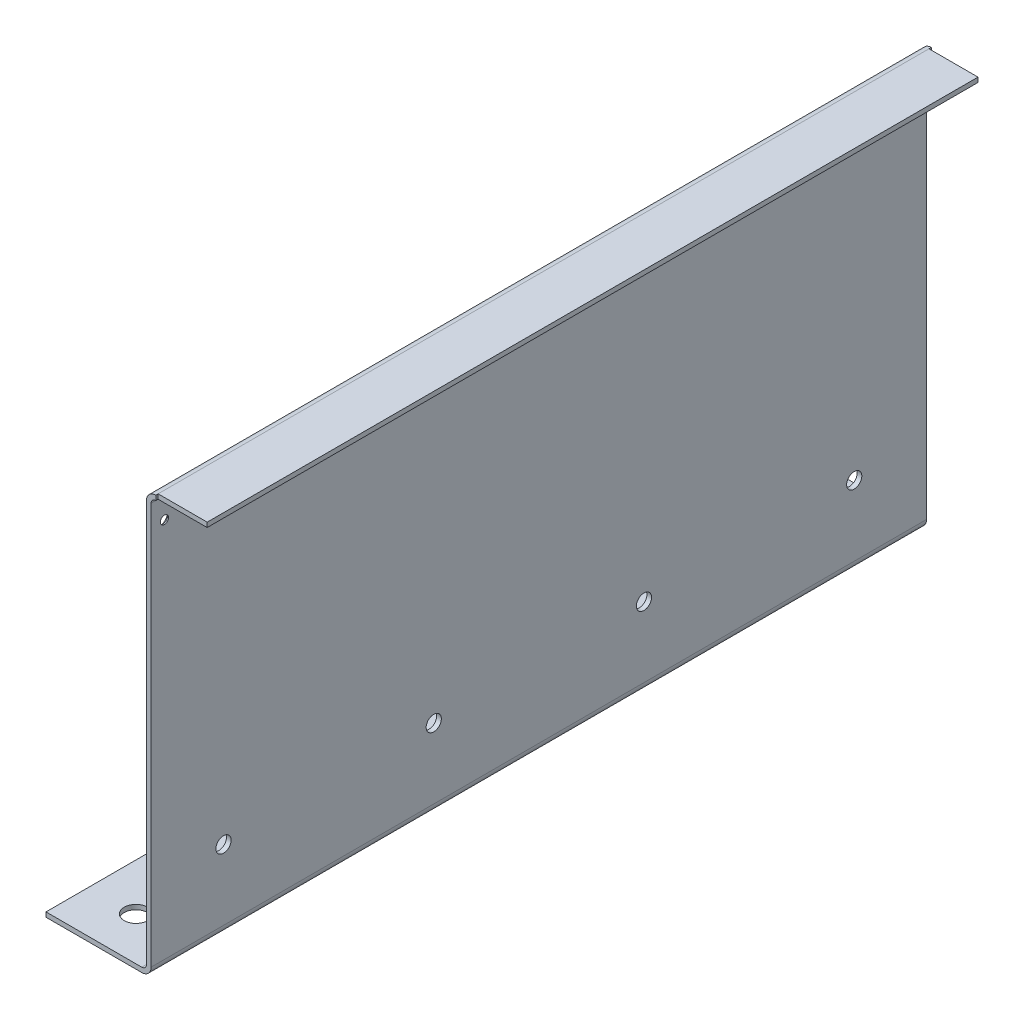
SolidWorks part; units mm, degrees
ref_plane "Спереди" through (0, 0, 0) normal (0, 0, 1) x (1, 0, 0)
ref_plane "Сверху" through (0, 0, 0) normal (0, 1, 0) x (1, 0, 0)
ref_plane "Справа" through (0, 0, 0) normal (1, 0, 0) x (0, 0, -1)
sketch "Эскиз1" plane through (0, 0, 0) normal (0, 0, 1) x (1, 0, 0)
  line L0 (0, 0) -> (0, 82.8028) construction
  line L1 (-1, -68) -> (-1, 104)
  line L4 (1, -68) -> (1, 104)
  line L5 (0, 0) -> (50.6989, 0) construction
  line L6 (3, 106) -> (24, 106)
  line L7 (3, 108) -> (24, 108)
  line L9 (-3, -72) -> (-44, -72)
  line L10 (24, 108) -> (24, 106)
  line L12 (-3, -70) -> (-44, -70)
  line L13 (-44, -72) -> (-44, -70)
  arc A0 (3, 106) -> (1, 104) centre (3, 104) ccw
  arc A1 (-3, -70) -> (-1, -68) centre (-3, -68) ccw
  arc A2 (-3, -72) -> (1, -68) centre (-3, -68) ccw
  arc A3 (-1, 104) -> (3, 108) centre (3, 104) cw
  dimension "D7" = 2
  dimension "D8" = 4
  dimension "D1" = 2
  dimension "D2" = 180
  dimension "D3" = 2
  dimension "D4" = 25
  dimension "D5" = 45
  dimension "D6" = 2
extrude "Вытянуть1" add sketch "Эскиз1" along normal blind 332
sketch "Эскиз2" plane through (-1, 0, 0) normal (-1, 0, 0) x (0, 0, 1)
  line L0 (-8.3976, -38) -> (341.3976, -38) construction
  line L1 (332, -72) -> (0, -72) construction
  line L2 (166, 127.3322) -> (166, -99.1297) construction
  line L3 (0, 104) -> (0, -68) construction
  line L4 (332, 104) -> (332, -68) construction
  circle A0 centre (31, -38) radius 3.25
  circle A1 centre (121, -38) radius 3.25
  circle A2 centre (211, -38) radius 3.25
  circle A3 centre (301, -38) radius 3.25
  dimension "D2" = 90
  dimension "D4" = 6.5
  dimension "D1" = 34
  dimension "D3" = 31
extrude "Вырез-Вытянуть1" cut sketch "Эскиз2" against normal blind 5
sketch "Эскиз3" plane through (0, -70, 0) normal (0, 1, 0) x (1, 0, 0)
  line L0 (-79.1329, -166) -> (76.6618, -166) construction
  line L1 (-24, 28.7881) -> (-24, -351.4381) construction
  line L4 (-44, -332) -> (-44, 0) construction
  line L5 (-3, 0) -> (-44, 0) construction
  line L6 (-3, -332) -> (-44, -332) construction
  circle A0 centre (-24, -18.5) radius 5
  circle A1 centre (-24, -313.5) radius 5
  dimension "D2" = 295
  dimension "D3" = 10
  dimension "D1" = 20
extrude "Вырез-Вытянуть2" cut sketch "Эскиз3" against normal blind 5
sketch "Эскиз4" plane through (0, 108, 0) normal (0, 1, 0) x (1, 0, 0)
  line L0 (-77.123, -166) -> (75.0406, -166) construction
  line L1 (24, 0) -> (3, 0) construction
  line L2 (24, -332) -> (3, -332) construction
  line L3 (3, -332) -> (3, 0) construction
  line L4 (3, -1) -> (29.1791, -1)
  line L5 (3, -1) -> (3, 2.2573)
  line L6 (3, 2.2573) -> (29.1791, 2.2573)
  line L7 (29.1791, -1) -> (29.1791, 2.2573)
  line L8 (24, -332) -> (24, 0) construction
  line L9 (29.1791, -331) -> (29.1791, -334.2573)
  line L10 (3, -334.2573) -> (29.1791, -334.2573)
  line L11 (3, -331) -> (3, -334.2573)
  line L12 (3, -331) -> (29.1791, -331)
  dimension "D1" = 1
  dimension "D2" = 21
extrude "Вырез-Вытянуть3" cut sketch "Эскиз4" against normal blind 10
sketch "Эскиз5" plane through (-1, 0, 0) normal (-1, 0, 0) x (0, 0, 1)
  line L0 (331, 108) -> (1, 108) construction
  line L1 (0, 104) -> (0, -68) construction
  line L2 (166, -112.0097) -> (166, 140.7956) construction
  line L3 (332, 104) -> (332, -68) construction
  circle A0 centre (5.7, 95) radius 1.75
  circle A1 centre (326.3, 95) radius 1.75
  dimension "D1" = 13
  dimension "D3" = 3.5
  dimension "D2" = 5.7
extrude "Вырез-Вытянуть4" cut sketch "Эскиз5" against normal blind 2.5
chamfer "Фаска1" distance 1.5 angle 45 2 edges at (-1, 96.75, 326.3) (-1, 93.25, 5.7)
